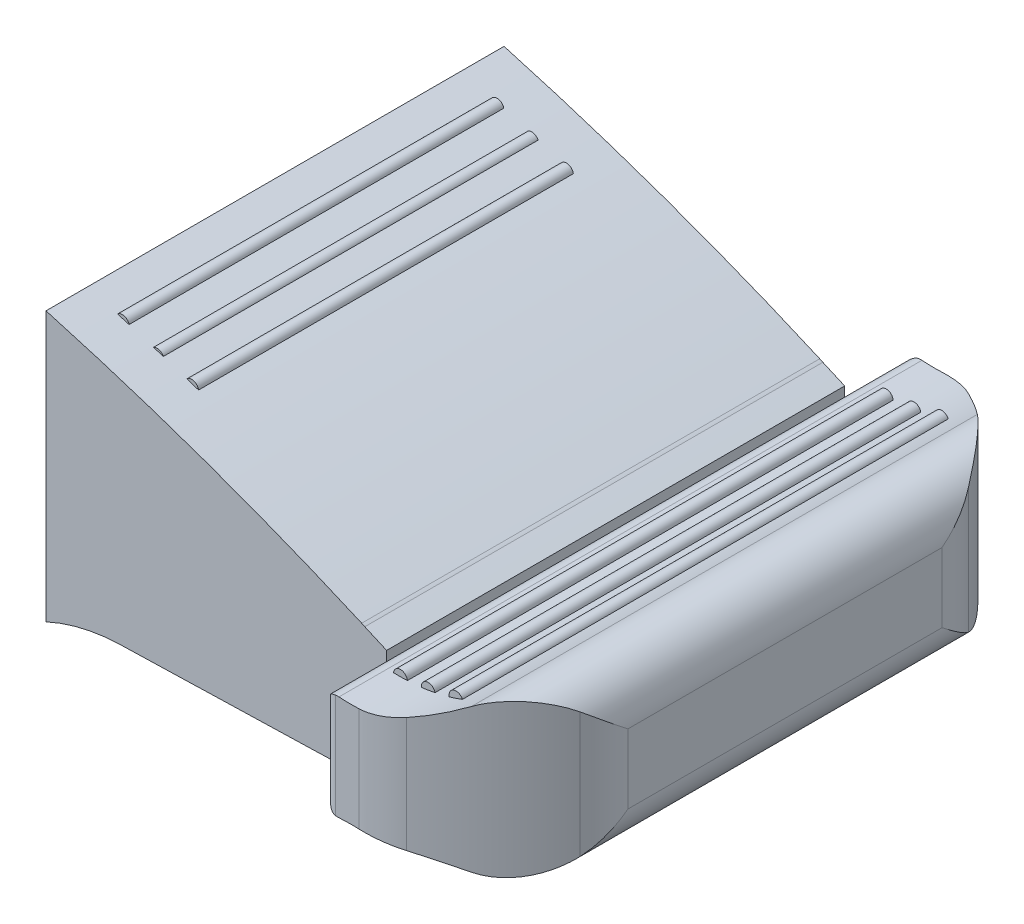
SolidWorks part; units mm, degrees
ref_plane "Front Plane" through (0, 0, 0) normal (0, 0, 1) x (1, 0, 0)
ref_plane "Top Plane" through (0, 0, 0) normal (0, 1, 0) x (1, 0, 0)
ref_plane "Right Plane" through (0, 0, 0) normal (1, 0, 0) x (0, 0, -1)
sketch "Sk_pedal_stem" plane through (0, 0, 0) normal (0, 0, 1) x (1, 0, 0)
  line L0 (62.5221, 30.2141) -> (62.5221, 54.862)
  line L1 (93.6879, 43.5356) -> (93.6879, 36.1917)
  line L2 (89.9843, 32.3832) -> (69.3113, 31.8056)
  arc A0 (62.5221, 54.862) -> (91.407, 44.5506) centre (3.5149, -156.0455) cw
  arc A1 (91.407, 44.5506) -> (91.692, 44.4111) centre (89.9041, 41.1181) cw
  arc A2 (91.692, 44.4111) -> (93.6879, 43.5356) centre (-1.0554, -169.7345) cw
  arc A3 (93.6879, 36.1917) -> (89.9843, 32.3832) centre (89.878, 36.1917) cw
  arc A4 (69.3113, 31.8056) -> (62.5221, 30.2141) centre (69.7959, 14.462) ccw
extrude "Ext_pedal_stem" add sketch "Sk_pedal_stem" along normal mid plane 41.91
sketch "Sk_foot_side" plane through (0, 0, 0) normal (0, 0, 1) x (1, 0, 0)
  line L0 (93.6879, 35.0718) -> (93.6879, 42.1188)
  line L1 (109.1819, 41.7703) -> (109.1819, 35.4203)
  arc A0 (93.6879, 42.1188) -> (95.0435, 43.386) centre (94.958, 42.1187) cw
  arc A1 (95.0435, 43.386) -> (103.6422, 45.165) centre (96.1573, 59.6725) ccw
  arc A2 (103.6422, 45.165) -> (109.1819, 41.7703) centre (105.3719, 41.7703) cw
  arc A3 (109.1819, 35.4203) -> (103.6422, 32.0256) centre (105.3719, 35.4203) cw
  arc A4 (103.6422, 32.0256) -> (95.0435, 33.8046) centre (96.1543, 17.5038) ccw
  arc A5 (95.0435, 33.8046) -> (93.6879, 35.0718) centre (94.9578, 35.0717) cw
extrude "Ext_foot_side" add sketch "Sk_foot_side" along normal mid plane 53.34
sketch "Sk_foot_plan_trim" plane through (0, 0, 0) normal (0, 1, 0) x (1, 0, 0)
  line L0 (94.7039, -26.67) -> (96.8731, -26.67)
  line L1 (109.1819, -14.3688) -> (109.1819, 14.3688)
  line L2 (96.8731, 26.67) -> (94.7039, 26.67)
  line L3 (93.6879, 25.654) -> (93.6879, 40.64)
  line L4 (93.6879, 40.64) -> (119.38, 40.64)
  line L5 (119.38, 40.64) -> (119.38, -40.64)
  line L6 (119.38, -40.64) -> (93.6879, -40.64)
  line L7 (93.6879, -40.64) -> (93.6879, -25.654)
  arc A0 (93.6879, -25.654) -> (94.7039, -26.67) centre (94.7039, -25.654) ccw
  arc A1 (96.8731, -26.67) -> (100.2563, -25.6939) centre (96.8727, -20.3173) ccw
  arc A2 (100.2563, -25.6939) -> (108.201, -17.7602) centre (86.7314, -4.2057) ccw
  arc A3 (108.201, -17.7602) -> (109.1819, -14.3688) centre (102.8373, -14.3712) ccw
  arc A4 (109.1819, 14.3688) -> (108.201, 17.7602) centre (102.826, 14.3679) ccw
  arc A5 (108.201, 17.7602) -> (100.2563, 25.6939) centre (86.7187, 4.1929) ccw
  arc A6 (100.2563, 25.6939) -> (96.8731, 26.67) centre (96.8742, 20.3224) ccw
  arc A7 (94.7039, 26.67) -> (93.6879, 25.654) centre (94.7039, 25.654) ccw
extrude "Cut_foot_plan" cut sketch "Sk_foot_plan_trim" against normal through all and the other way through all
sketch "Sk_ribs_stem" plane through (0, 0, 0) normal (0, 0, 1) x (1, 0, 0)
  circle A0 centre (65.6971, 53.6118) radius 0.635
  circle A1 centre (68.8721, 52.5323) radius 0.635
  circle A2 centre (72.0471, 51.6484) radius 0.635
extrude "Ext_ribs_stem" add sketch "Sk_ribs_stem" along normal mid plane 34.29
sketch "Sk_ribs_foot" plane through (0, 0, 0) normal (0, 0, 1) x (1, 0, 0)
  circle A0 centre (96.2279, 43.2943) radius 0.635
  circle A1 centre (98.7679, 43.5356) radius 0.635
  circle A2 centre (101.3079, 44.135) radius 0.635
extrude "Ext_ribs_foot" add sketch "Sk_ribs_foot" along normal mid plane 44.45
